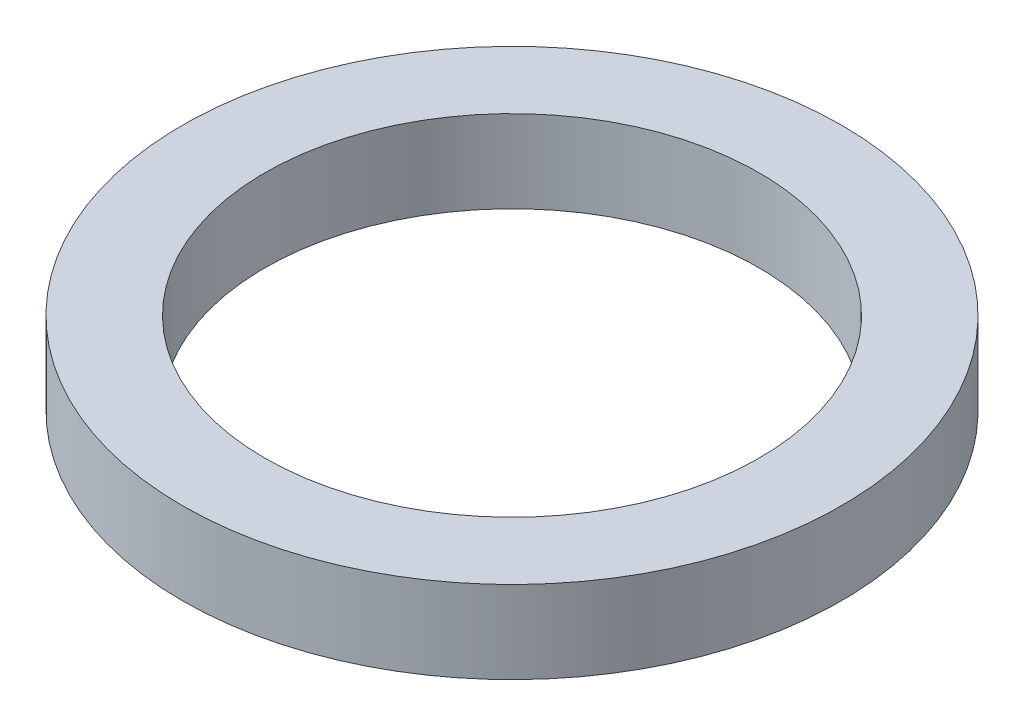
SolidWorks part; units mm, degrees
ref_plane "Front Plane" through (0, 0, 0) normal (0, 0, 1) x (1, 0, 0)
ref_plane "Top Plane" through (0, 0, 0) normal (0, 1, 0) x (1, 0, 0)
ref_plane "Right Plane" through (0, 0, 0) normal (1, 0, 0) x (0, 0, -1)
sketch "Sketch1" plane through (0, 0, 0) normal (0, 1, 0) x (1, 0, 0)
  circle A0 centre (0, 0) radius 3
  circle A1 centre (0, 0) radius 4
  dimension "D1" = 8
  dimension "D2" = 6
extrude "Boss-Extrude1" add sketch "Sketch1" along normal blind 1
